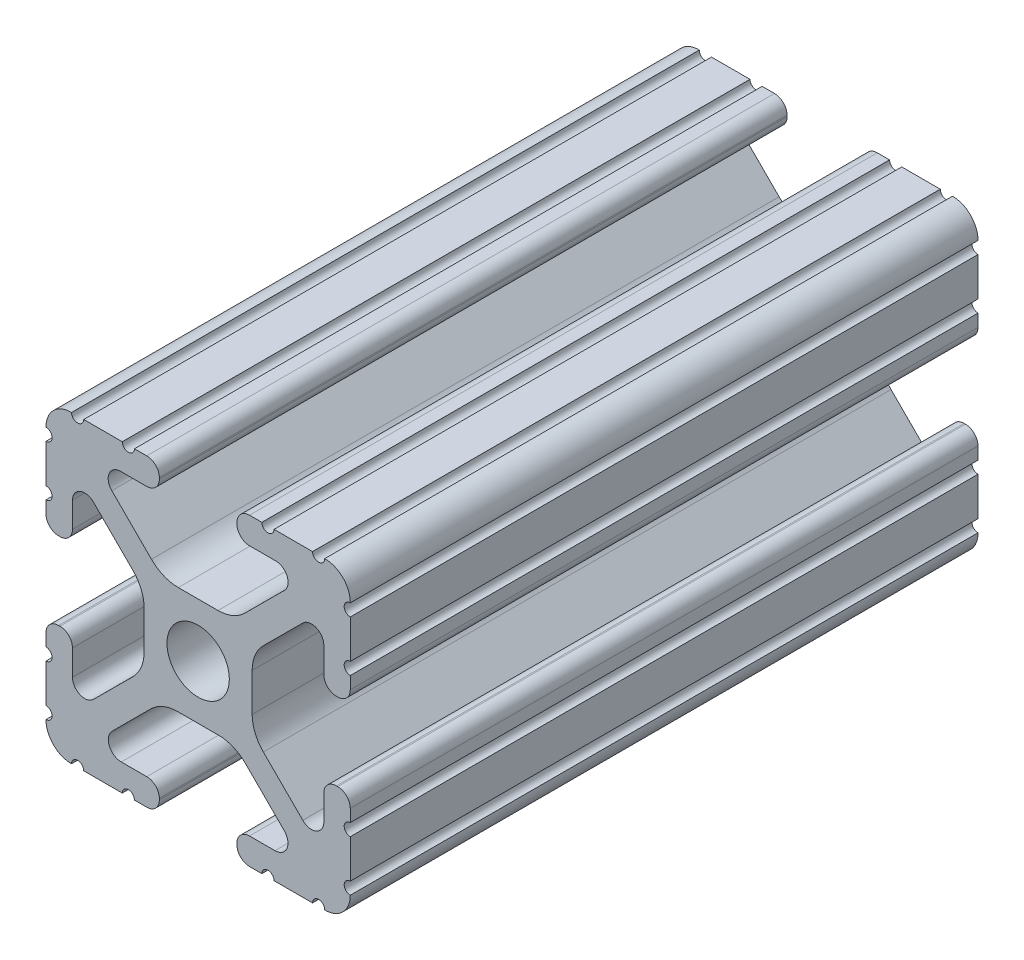
SolidWorks part; units mm, degrees
ref_plane "Front Plane" through (0, 0, 0) normal (0, 0, 1) x (1, 0, 0)
ref_plane "Top Plane" through (0, 0, 0) normal (0, 1, 0) x (1, 0, 0)
ref_plane "Right Plane" through (0, 0, 0) normal (1, 0, 0) x (0, 0, -1)
sketch "Sketch1" plane through (0, 0, 0) normal (0, 0, 1) x (1, 0, 0)
  line L88 (-7.1797, -8.6452) -> (-3.9523, -5.4237)
  line L89 (-1.7093, -4.4958) -> (1.7093, -4.4958)
  line L90 (3.9523, -5.4237) -> (7.1797, -8.6452)
  line L91 (6.4164, -10.4902) -> (4.2875, -10.4902)
  line L92 (3.2385, -11.5392) -> (3.2385, -11.651)
  line L93 (4.2875, -12.7) -> (5.3171, -12.7)
  line L94 (6.3331, -12.7) -> (9.5504, -12.7)
  line L95 (12.7, -9.5504) -> (12.7, -6.3331)
  line L96 (12.7, -5.3171) -> (12.7, -4.2875)
  line L97 (11.651, -3.2385) -> (11.5392, -3.2385)
  line L98 (10.4902, -4.2875) -> (10.4902, -6.4021)
  line L99 (8.7371, -7.1294) -> (5.441, -3.8408)
  line L100 (4.5085, -1.5932) -> (4.5085, 1.5932)
  line L101 (5.441, 3.8408) -> (8.7371, 7.1294)
  line L102 (10.4902, 6.4021) -> (10.4902, 4.2875)
  line L103 (11.5392, 3.2385) -> (11.651, 3.2385)
  line L104 (12.7, 4.2875) -> (12.7, 5.3171)
  line L105 (12.7, 6.3331) -> (12.7, 9.5504)
  line L106 (9.5504, 12.7) -> (6.3331, 12.7)
  line L107 (5.3171, 12.7) -> (4.2875, 12.7)
  line L108 (3.2385, 11.651) -> (3.2385, 11.5392)
  line L109 (4.2875, 10.4902) -> (6.4768, 10.4902)
  line L110 (7.207, 8.7244) -> (3.8983, 5.4232)
  line L111 (1.6558, 4.4958) -> (-1.6558, 4.4958)
  line L112 (-3.8983, 5.4232) -> (-7.207, 8.7244)
  line L113 (-6.4768, 10.4902) -> (-4.2875, 10.4902)
  line L114 (-3.2385, 11.5392) -> (-3.2385, 11.651)
  line L115 (-4.2875, 12.7) -> (-5.3171, 12.7)
  line L116 (-6.3331, 12.7) -> (-9.5504, 12.7)
  line L117 (-12.7, 9.5504) -> (-12.7, 6.3331)
  line L118 (-12.7, 5.3171) -> (-12.7, 4.2875)
  line L119 (-11.651, 3.2385) -> (-11.5392, 3.2385)
  line L120 (-10.4902, 4.2875) -> (-10.4902, 6.4021)
  line L121 (-8.7371, 7.1294) -> (-5.441, 3.8408)
  line L122 (-4.5085, 1.5932) -> (-4.5085, -1.5932)
  line L123 (-5.441, -3.8408) -> (-8.7371, -7.1294)
  line L124 (-10.4902, -6.4021) -> (-10.4902, -4.2875)
  line L125 (-11.5392, -3.2385) -> (-11.651, -3.2385)
  line L126 (-12.7, -4.2875) -> (-12.7, -5.3171)
  line L127 (-12.7, -6.3331) -> (-12.7, -9.5504)
  line L128 (-9.5504, -12.7) -> (-6.3331, -12.7)
  line L129 (-5.3171, -12.7) -> (-4.2875, -12.7)
  line L130 (-3.2385, -11.651) -> (-3.2385, -11.5392)
  line L131 (-4.2875, -10.4902) -> (-6.4164, -10.4902)
  circle A1 centre (0, 0) radius 2.6035
  arc A104 (-7.1797, -8.6452) -> (-6.4164, -10.4902) centre (-6.4164, -9.4098) ccw
  arc A105 (-1.7093, -4.4958) -> (-3.9523, -5.4237) centre (-1.7093, -7.6708) ccw
  arc A106 (3.9523, -5.4237) -> (1.7093, -4.4958) centre (1.7093, -7.6708) ccw
  arc A107 (6.4164, -10.4902) -> (7.1797, -8.6452) centre (6.4164, -9.4098) ccw
  arc A108 (4.2875, -10.4902) -> (3.2385, -11.5392) centre (4.2875, -11.5392) ccw
  arc A109 (3.2385, -11.651) -> (4.2875, -12.7) centre (4.2875, -11.651) ccw
  arc A110 (6.3331, -12.7) -> (5.3171, -12.7) centre (5.8251, -12.7) ccw
  arc A111 (10.5664, -12.6998) -> (9.5504, -12.7) centre (10.0584, -12.7) ccw
  arc A112 (10.5664, -12.6998) -> (12.6998, -10.5664) centre (10.5918, -10.5918) ccw
  arc A113 (12.7, -9.5504) -> (12.6998, -10.5664) centre (12.7, -10.0584) ccw
  arc A114 (12.7, -5.3171) -> (12.7, -6.3331) centre (12.7, -5.8251) ccw
  arc A115 (12.7, -4.2875) -> (11.651, -3.2385) centre (11.651, -4.2875) ccw
  arc A116 (11.5392, -3.2385) -> (10.4902, -4.2875) centre (11.5392, -4.2875) ccw
  arc A117 (8.7371, -7.1294) -> (10.4902, -6.4021) centre (9.4628, -6.4021) ccw
  arc A118 (4.5085, -1.5932) -> (5.441, -3.8408) centre (7.6835, -1.5932) ccw
  arc A119 (5.441, 3.8408) -> (4.5085, 1.5932) centre (7.6835, 1.5932) ccw
  arc A120 (10.4902, 6.4021) -> (8.7371, 7.1294) centre (9.4628, 6.4021) ccw
  arc A121 (10.4902, 4.2875) -> (11.5392, 3.2385) centre (11.5392, 4.2875) ccw
  arc A122 (11.651, 3.2385) -> (12.7, 4.2875) centre (11.651, 4.2875) ccw
  arc A123 (12.7, 6.3331) -> (12.7, 5.3171) centre (12.7, 5.8251) ccw
  arc A124 (12.6998, 10.5664) -> (12.7, 9.5504) centre (12.7, 10.0584) ccw
  arc A125 (12.6998, 10.5664) -> (10.5664, 12.6998) centre (10.5918, 10.5918) ccw
  arc A126 (9.5504, 12.7) -> (10.5664, 12.6998) centre (10.0584, 12.7) ccw
  arc A127 (5.3171, 12.7) -> (6.3331, 12.7) centre (5.8251, 12.7) ccw
  arc A128 (4.2875, 12.7) -> (3.2385, 11.651) centre (4.2875, 11.651) ccw
  arc A129 (3.2385, 11.5392) -> (4.2875, 10.4902) centre (4.2875, 11.5392) ccw
  arc A130 (7.207, 8.7244) -> (6.4768, 10.4902) centre (6.4768, 9.4563) ccw
  arc A131 (1.6558, 4.4958) -> (3.8983, 5.4232) centre (1.6558, 7.6708) ccw
  arc A132 (-3.8983, 5.4232) -> (-1.6558, 4.4958) centre (-1.6558, 7.6708) ccw
  arc A133 (-6.4768, 10.4902) -> (-7.207, 8.7244) centre (-6.4768, 9.4563) ccw
  arc A134 (-4.2875, 10.4902) -> (-3.2385, 11.5392) centre (-4.2875, 11.5392) ccw
  arc A135 (-3.2385, 11.651) -> (-4.2875, 12.7) centre (-4.2875, 11.651) ccw
  arc A136 (-6.3331, 12.7) -> (-5.3171, 12.7) centre (-5.8251, 12.7) ccw
  arc A137 (-10.5664, 12.6998) -> (-9.5504, 12.7) centre (-10.0584, 12.7) ccw
  arc A138 (-10.5664, 12.6998) -> (-12.6998, 10.5664) centre (-10.5918, 10.5918) ccw
  arc A139 (-12.7, 9.5504) -> (-12.6998, 10.5664) centre (-12.7, 10.0584) ccw
  arc A140 (-12.7, 5.3171) -> (-12.7, 6.3331) centre (-12.7, 5.8251) ccw
  arc A141 (-12.7, 4.2875) -> (-11.651, 3.2385) centre (-11.651, 4.2875) ccw
  arc A142 (-11.5392, 3.2385) -> (-10.4902, 4.2875) centre (-11.5392, 4.2875) ccw
  arc A143 (-8.7371, 7.1294) -> (-10.4902, 6.4021) centre (-9.4628, 6.4021) ccw
  arc A144 (-4.5085, 1.5932) -> (-5.441, 3.8408) centre (-7.6835, 1.5932) ccw
  arc A145 (-5.441, -3.8408) -> (-4.5085, -1.5932) centre (-7.6835, -1.5932) ccw
  arc A146 (-10.4902, -6.4021) -> (-8.7371, -7.1294) centre (-9.4628, -6.4021) ccw
  arc A147 (-10.4902, -4.2875) -> (-11.5392, -3.2385) centre (-11.5392, -4.2875) ccw
  arc A148 (-11.651, -3.2385) -> (-12.7, -4.2875) centre (-11.651, -4.2875) ccw
  arc A149 (-12.7, -6.3331) -> (-12.7, -5.3171) centre (-12.7, -5.8251) ccw
  arc A150 (-12.6998, -10.5664) -> (-12.7, -9.5504) centre (-12.7, -10.0584) ccw
  arc A151 (-12.6998, -10.5664) -> (-10.5664, -12.6998) centre (-10.5918, -10.5918) ccw
  arc A152 (-9.5504, -12.7) -> (-10.5664, -12.6998) centre (-10.0584, -12.7) ccw
  arc A153 (-5.3171, -12.7) -> (-6.3331, -12.7) centre (-5.8251, -12.7) ccw
  arc A154 (-4.2875, -12.7) -> (-3.2385, -11.651) centre (-4.2875, -11.651) ccw
  arc A155 (-3.2385, -11.5392) -> (-4.2875, -10.4902) centre (-4.2875, -11.5392) ccw
extrude "Boss-Extrude1" add sketch "Sketch1" along normal mid plane 52.4
